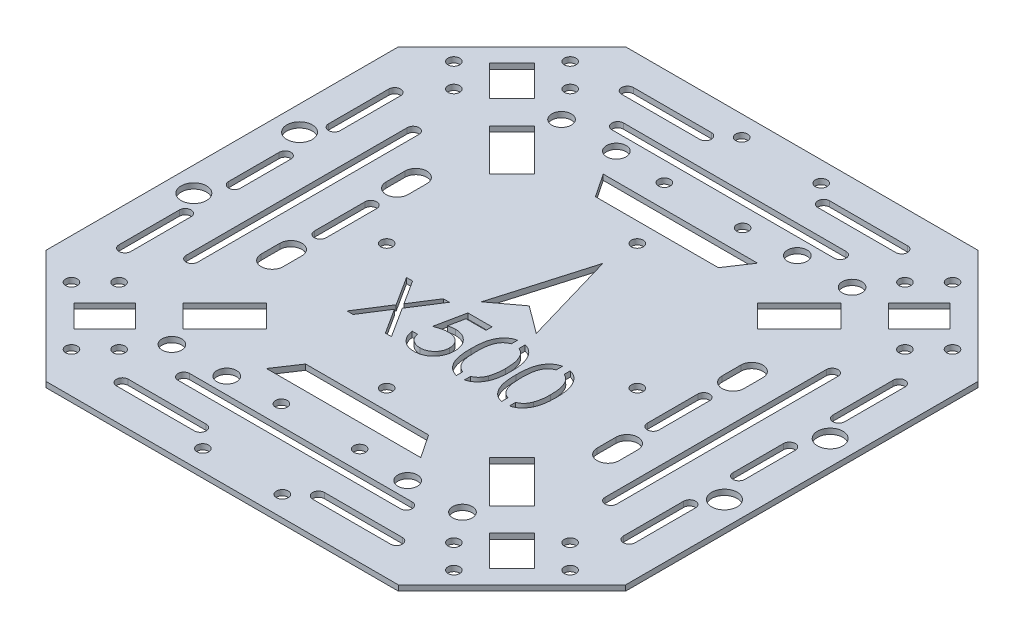
SolidWorks part; units mm, degrees
material "Thornel Mat VMA"
ref_plane "Front Plane" through (0, 0, 0) normal (0, 0, 1) x (1, 0, 0)
ref_plane "Top Plane" through (0, 0, 0) normal (0, 1, 0) x (1, 0, 0)
ref_plane "Right Plane" through (0, 0, 0) normal (1, 0, 0) x (0, 0, -1)
sketch "Sketch1" plane through (0, 0, 0) normal (0, 1, 0) x (1, 0, 0)
  line L0 (-74, 45) -> (-45, 74)
  line L1 (-45, 74) -> (45, 74)
  line L2 (-74, 45) -> (-74, -45)
  line L3 (-45, -74) -> (45, -74)
  line L4 (74, 45) -> (74, -45)
  line L5 (45, 74) -> (74, 45)
  line L6 (74, -45) -> (45, -74)
  line L7 (-45, -74) -> (-74, -45)
  line L8 (0, -51.6391) -> (0, 51.6391) construction
  line L9 (-43.1025, 0) -> (43.1025, 0) construction
  point P0 (0, -74)
  point P11 (0, 74)
  point P12 (-74, 0)
  point P15 (74, 0)
  dimension "D1" = 148
  dimension "D2" = 90
  dimension "D3" = 45
extrude "Boss-Extrude1" add sketch "Sketch1" along normal mid plane 1.4
sketch "Sketch3" plane through (0, 0.7, 0) normal (0, 1, 0) x (1, 0, 0)
  line L0 (-50.9087, 45.1811) -> (-58.7575, 53.03)
  line L1 (-50.9087, 45.1811) -> (-45.1811, 50.9087)
  line L2 (-58.7575, 53.03) -> (-53.03, 58.7575)
  line L3 (-45.1811, 50.9087) -> (-53.03, 58.7575)
  line L4 (-44.8982, 39.1707) -> (-34.2209, 28.4934)
  line L5 (-44.8982, 39.1707) -> (-39.1707, 44.8982)
  line L6 (-34.2209, 28.4934) -> (-28.4934, 34.2209)
  line L7 (-39.1707, 44.8982) -> (-28.4934, 34.2209)
  line L8 (0, 0) -> (-48.0449, 48.0449) construction
  line L9 (-63.6719, 48.8227) -> (-57.5908, 42.7416) construction
  line L10 (-45, 74) -> (-74, 45) construction
  line L11 (-48.8227, 63.6719) -> (-42.7416, 57.5908) construction
  line L12 (-63.6719, 48.8227) -> (-48.8227, 63.6719) construction
  line L13 (45.1811, 50.9087) -> (53.03, 58.7575)
  line L14 (45.1811, 50.9087) -> (50.9087, 45.1811)
  line L15 (53.03, 58.7575) -> (58.7575, 53.03)
  line L16 (50.9087, 45.1811) -> (58.7575, 53.03)
  line L17 (39.1707, 44.8982) -> (28.4934, 34.2209)
  line L18 (39.1707, 44.8982) -> (44.8982, 39.1707)
  line L19 (28.4934, 34.2209) -> (34.2209, 28.4934)
  line L20 (44.8982, 39.1707) -> (34.2209, 28.4934)
  line L21 (48.8227, 63.6719) -> (42.7416, 57.5908) construction
  line L22 (63.6719, 48.8227) -> (57.5908, 42.7416) construction
  line L23 (48.8227, 63.6719) -> (63.6719, 48.8227) construction
  line L24 (50.9087, -45.1811) -> (58.7575, -53.03)
  line L25 (50.9087, -45.1811) -> (45.1811, -50.9087)
  line L26 (58.7575, -53.03) -> (53.03, -58.7575)
  line L27 (45.1811, -50.9087) -> (53.03, -58.7575)
  line L28 (44.8982, -39.1707) -> (34.2209, -28.4934)
  line L29 (44.8982, -39.1707) -> (39.1707, -44.8982)
  line L30 (34.2209, -28.4934) -> (28.4934, -34.2209)
  line L31 (39.1707, -44.8982) -> (28.4934, -34.2209)
  line L32 (63.6719, -48.8227) -> (57.5908, -42.7416) construction
  line L33 (48.8227, -63.6719) -> (42.7416, -57.5908) construction
  line L34 (63.6719, -48.8227) -> (48.8227, -63.6719) construction
  line L35 (-45.1811, -50.9087) -> (-53.03, -58.7575)
  line L36 (-45.1811, -50.9087) -> (-50.9087, -45.1811)
  line L37 (-53.03, -58.7575) -> (-58.7575, -53.03)
  line L38 (-50.9087, -45.1811) -> (-58.7575, -53.03)
  line L39 (-39.1707, -44.8982) -> (-28.4934, -34.2209)
  line L40 (-39.1707, -44.8982) -> (-44.8982, -39.1707)
  line L41 (-28.4934, -34.2209) -> (-34.2209, -28.4934)
  line L42 (-44.8982, -39.1707) -> (-34.2209, -28.4934)
  line L43 (-48.8227, -63.6719) -> (-42.7416, -57.5908) construction
  line L44 (-63.6719, -48.8227) -> (-57.5908, -42.7416) construction
  line L45 (-48.8227, -63.6719) -> (-63.6719, -48.8227) construction
  line L46 (0, -0.77) -> (0, 0.77) construction
  line L47 (-0.77, 0) -> (0.77, 0) construction
  circle A0 centre (-48.8227, 63.6719) radius 1.5
  circle A1 centre (-63.6719, 48.8227) radius 1.5
  circle A2 centre (-57.5908, 42.7416) radius 1.5
  circle A3 centre (-42.7416, 57.5908) radius 1.5
  circle A4 centre (63.6719, 48.8227) radius 1.5
  circle A5 centre (48.8227, 63.6719) radius 1.5
  circle A6 centre (42.7416, 57.5908) radius 1.5
  circle A7 centre (57.5908, 42.7416) radius 1.5
  circle A8 centre (48.8227, -63.6719) radius 1.5
  circle A9 centre (63.6719, -48.8227) radius 1.5
  circle A10 centre (57.5908, -42.7416) radius 1.5
  circle A11 centre (42.7416, -57.5908) radius 1.5
  circle A12 centre (-63.6719, -48.8227) radius 1.5
  circle A13 centre (-48.8227, -63.6719) radius 1.5
  circle A14 centre (-42.7416, -57.5908) radius 1.5
  circle A15 centre (-57.5908, -42.7416) radius 1.5
  point P20 (-48.0449, 48.0449)
  point P21 (-55.8938, 55.8938)
  point P22 (-42.0345, 42.0345)
  point P23 (-31.3572, 31.3572)
  point P27 (-59.5, 59.5)
  point P77 (0, 0)
  dimension "D7" = 3
  dimension "D1" = 8.5
  dimension "D2" = 5.1
  dimension "D3" = 11.1
  dimension "D4" = 15.1
  dimension "D5" = 8.1
  dimension "D6" = 8.1
  dimension "D8" = 21
  dimension "D9" = 10.5
  dimension "D10" = 4.6
  dimension "D11" = 8.6
  dimension "D12" = 4
extrude "Cut-Extrude1" cut sketch "Sketch3" against normal through all
sketch "Sketch4" plane through (0, 0.7, 0) normal (0, 1, 0) x (1, 0, 0)
  line L0 (-53.5, 28.25) -> (-53.5, -28.25) construction
  line L3 (-52, 28.25) -> (-52, -28.25)
  line L6 (-55, 28.25) -> (-55, -28.25)
  line L9 (-64.4, 34.45) -> (-64.4, 19.05) construction
  line L12 (-62.9, 34.45) -> (-62.9, 19.05)
  line L15 (-65.9, 34.45) -> (-65.9, 19.05)
  line L18 (-64.4, -19.05) -> (-64.4, -34.45) construction
  line L21 (-74, 45) -> (-74, -45) construction
  line L22 (-62.9, -19.05) -> (-62.9, -34.45)
  line L23 (-65.9, -19.05) -> (-65.9, -34.45)
  line L24 (-64.4, 6.45) -> (-64.4, -6.45) construction
  line L25 (-62.9, 6.45) -> (-62.9, -6.45)
  line L26 (-65.9, 6.45) -> (-65.9, -6.45)
  line L27 (-42.9, 18.35) -> (-42.9, 13.55) construction
  line L28 (-40.1, 18.35) -> (-40.1, 13.55)
  line L29 (-45.7, 18.35) -> (-45.7, 13.55)
  line L30 (-42.5, 6.45) -> (-42.5, -6.45) construction
  line L31 (-41, 6.45) -> (-41, -6.45)
  line L32 (-44, 6.45) -> (-44, -6.45)
  line L33 (-42.9, -13.55) -> (-42.9, -18.35) construction
  line L34 (-40.1, -13.55) -> (-40.1, -18.35)
  line L35 (-45.7, -13.55) -> (-45.7, -18.35)
  line L36 (-0.77, 0) -> (0.77, 0) construction
  line L37 (-67.75, 13.5) -> (-67.75, -13.5) construction
  line L38 (-42.9, 13.55) -> (-42.9, -13.55) construction
  line L39 (0, -0.77) -> (0, 0.77) construction
  line L40 (53.5, 28.25) -> (53.5, -28.25) construction
  line L41 (52, 28.25) -> (52, -28.25)
  line L42 (55, 28.25) -> (55, -28.25)
  line L43 (64.4, 34.45) -> (64.4, 19.05) construction
  line L44 (62.9, 34.45) -> (62.9, 19.05)
  line L45 (65.9, 34.45) -> (65.9, 19.05)
  line L46 (64.4, -19.05) -> (64.4, -34.45) construction
  line L47 (62.9, -19.05) -> (62.9, -34.45)
  line L48 (65.9, -19.05) -> (65.9, -34.45)
  line L49 (64.4, 6.45) -> (64.4, -6.45) construction
  line L50 (62.9, 6.45) -> (62.9, -6.45)
  line L51 (65.9, 6.45) -> (65.9, -6.45)
  line L52 (42.9, 18.35) -> (42.9, 13.55) construction
  line L53 (40.1, 18.35) -> (40.1, 13.55)
  line L54 (45.7, 18.35) -> (45.7, 13.55)
  line L55 (42.5, 6.45) -> (42.5, -6.45) construction
  line L56 (41, 6.45) -> (41, -6.45)
  line L57 (44, 6.45) -> (44, -6.45)
  line L58 (42.9, -13.55) -> (42.9, -18.35) construction
  line L59 (40.1, -13.55) -> (40.1, -18.35)
  line L60 (45.7, -13.55) -> (45.7, -18.35)
  line L61 (42.9, 13.55) -> (42.9, -13.55) construction
  line L62 (67.75, 13.5) -> (67.75, -13.5) construction
  arc A17 (-52, 28.25) -> (-55, 28.25) centre (-53.5, 28.25) ccw
  arc A18 (-55, -28.25) -> (-52, -28.25) centre (-53.5, -28.25) ccw
  arc A19 (-62.9, 34.45) -> (-65.9, 34.45) centre (-64.4, 34.45) ccw
  arc A20 (-65.9, 19.05) -> (-62.9, 19.05) centre (-64.4, 19.05) ccw
  arc A21 (-62.9, -19.05) -> (-65.9, -19.05) centre (-64.4, -19.05) ccw
  arc A22 (-65.9, -34.45) -> (-62.9, -34.45) centre (-64.4, -34.45) ccw
  arc A23 (-62.9, 6.45) -> (-65.9, 6.45) centre (-64.4, 6.45) ccw
  arc A24 (-65.9, -6.45) -> (-62.9, -6.45) centre (-64.4, -6.45) ccw
  arc A25 (-40.1, 18.35) -> (-45.7, 18.35) centre (-42.9, 18.35) ccw
  arc A26 (-45.7, 13.55) -> (-40.1, 13.55) centre (-42.9, 13.55) ccw
  arc A27 (-41, 6.45) -> (-44, 6.45) centre (-42.5, 6.45) ccw
  arc A28 (-44, -6.45) -> (-41, -6.45) centre (-42.5, -6.45) ccw
  arc A29 (-40.1, -13.55) -> (-45.7, -13.55) centre (-42.9, -13.55) ccw
  arc A30 (-45.7, -18.35) -> (-40.1, -18.35) centre (-42.9, -18.35) ccw
  circle A31 centre (-67.75, 13.5) radius 3.25
  circle A32 centre (-67.75, -13.5) radius 3.25
  circle A33 centre (-32, 0) radius 1.5
  arc A34 (52, 28.25) -> (55, 28.25) centre (53.5, 28.25) cw
  arc A35 (55, -28.25) -> (52, -28.25) centre (53.5, -28.25) cw
  arc A36 (62.9, 34.45) -> (65.9, 34.45) centre (64.4, 34.45) cw
  arc A37 (65.9, 19.05) -> (62.9, 19.05) centre (64.4, 19.05) cw
  arc A38 (62.9, -19.05) -> (65.9, -19.05) centre (64.4, -19.05) cw
  arc A39 (65.9, -34.45) -> (62.9, -34.45) centre (64.4, -34.45) cw
  arc A40 (62.9, 6.45) -> (65.9, 6.45) centre (64.4, 6.45) cw
  arc A41 (65.9, -6.45) -> (62.9, -6.45) centre (64.4, -6.45) cw
  arc A42 (40.1, 18.35) -> (45.7, 18.35) centre (42.9, 18.35) cw
  arc A43 (45.7, 13.55) -> (40.1, 13.55) centre (42.9, 13.55) cw
  arc A44 (41, 6.45) -> (44, 6.45) centre (42.5, 6.45) cw
  arc A45 (44, -6.45) -> (41, -6.45) centre (42.5, -6.45) cw
  arc A46 (40.1, -13.55) -> (45.7, -13.55) centre (42.9, -13.55) cw
  arc A47 (45.7, -18.35) -> (40.1, -18.35) centre (42.9, -18.35) cw
  circle A48 centre (32, 0) radius 1.5
  circle A49 centre (67.75, -13.5) radius 3.25
  circle A50 centre (67.75, 13.5) radius 3.25
  point P2 (-53.5, 0)
  point P7 (-64.4, 26.75)
  point P14 (-64.4, -26.75)
  point P21 (-64.4, 0)
  point P28 (-42.9, 15.95)
  point P35 (-42.5, 0)
  point P42 (-42.9, -15.95)
  point P57 (-67.75, 0)
  point P60 (-42.9, 0)
  point P67 (53.5, 0)
  point P74 (64.4, 26.75)
  point P81 (64.4, -26.75)
  point P88 (64.4, 0)
  point P95 (42.9, 15.95)
  point P102 (42.5, 0)
  point P109 (42.9, -15.95)
  dimension "D9" = 6.5
  dimension "D18" = 3
  dimension "D1" = 3
  dimension "D2" = 8.1
  dimension "D3" = 12.6
  dimension "D4" = 12.6
  dimension "D5" = 12.9
  dimension "D6" = 15.4
  dimension "D7" = 19
  dimension "D8" = 56.5
  dimension "D10" = 6.25
  dimension "D11" = 27
  dimension "D12" = 30
  dimension "D13" = 12.9
  dimension "D14" = 5.6
  dimension "D15" = 4.8
  dimension "D16" = 28.3
  dimension "D17" = 27.1
  dimension "D19" = 42
extrude "Cut-Extrude2" cut sketch "Sketch4" against normal through all
sketch "Sketch5" plane through (0, 0.7, 0) normal (0, 1, 0) x (1, 0, 0)
  line L0 (-35, 64.5) -> (-15.1, 64.5) construction
  line L1 (-35, 66) -> (-15.1, 66)
  line L2 (-35, 63) -> (-15.1, 63)
  line L3 (15.1, 64.5) -> (35, 64.5) construction
  line L4 (15.1, 66) -> (35, 66)
  line L5 (15.1, 63) -> (35, 63)
  line L6 (-28.4, 55.4) -> (28.4, 55.4) construction
  line L7 (-28.4, 56.9) -> (28.4, 56.9)
  line L8 (-28.4, 53.9) -> (28.4, 53.9)
  line L9 (-19.7, 43) -> (-15.7, 37)
  line L10 (-15.7, 37) -> (15.7, 37)
  line L11 (15.7, 37) -> (19.7, 43)
  line L12 (19.7, 43) -> (-19.7, 43)
  line L13 (0, -0.77) -> (0, 0.77) construction
  line L14 (45, 74) -> (-45, 74) construction
  line L15 (-15.1, 64.5) -> (15.1, 64.5) construction
  line L16 (-10.15, 68.8) -> (10.15, 68.8) construction
  line L17 (-37.1, 49.75) -> (37.1, 49.75) construction
  line L18 (-10, 48.9) -> (10, 48.9) construction
  line L19 (-0.77, 0) -> (0.77, 0) construction
  line L20 (-35, -64.5) -> (-15.1, -64.5) construction
  line L21 (-35, -66) -> (-15.1, -66)
  line L22 (-35, -63) -> (-15.1, -63)
  line L23 (15.1, -64.5) -> (35, -64.5) construction
  line L24 (15.1, -66) -> (35, -66)
  line L25 (15.1, -63) -> (35, -63)
  line L26 (-28.4, -55.4) -> (28.4, -55.4) construction
  line L27 (-28.4, -56.9) -> (28.4, -56.9)
  line L28 (-28.4, -53.9) -> (28.4, -53.9)
  line L29 (-10, -48.9) -> (10, -48.9) construction
  line L30 (-37.1, -49.75) -> (37.1, -49.75) construction
  line L31 (-10.15, -68.8) -> (10.15, -68.8) construction
  line L32 (-15.1, -64.5) -> (15.1, -64.5) construction
  line L33 (19.7, -43) -> (-19.7, -43)
  line L34 (15.7, -37) -> (19.7, -43)
  line L35 (-15.7, -37) -> (15.7, -37)
  line L36 (-19.7, -43) -> (-15.7, -37)
  arc A0 (-35, 66) -> (-35, 63) centre (-35, 64.5) ccw
  arc A1 (-15.1, 63) -> (-15.1, 66) centre (-15.1, 64.5) ccw
  arc A2 (15.1, 66) -> (15.1, 63) centre (15.1, 64.5) ccw
  arc A3 (35, 63) -> (35, 66) centre (35, 64.5) ccw
  arc A4 (-28.4, 56.9) -> (-28.4, 53.9) centre (-28.4, 55.4) ccw
  arc A5 (28.4, 53.9) -> (28.4, 56.9) centre (28.4, 55.4) ccw
  circle A6 centre (-37.1, 49.75) radius 2.5
  circle A7 centre (-23.1, 49.75) radius 2.5
  circle A8 centre (-10, 48.9) radius 1.5
  circle A9 centre (10, 48.9) radius 1.5
  circle A10 centre (23.1, 49.75) radius 2.5
  circle A11 centre (37.1, 49.75) radius 2.5
  circle A12 centre (10.15, 68.8) radius 1.5
  circle A13 centre (-10.15, 68.8) radius 1.5
  circle A14 centre (0, 32) radius 1.5
  arc A15 (-35, -66) -> (-35, -63) centre (-35, -64.5) cw
  arc A16 (-15.1, -63) -> (-15.1, -66) centre (-15.1, -64.5) cw
  arc A17 (15.1, -66) -> (15.1, -63) centre (15.1, -64.5) cw
  arc A18 (35, -63) -> (35, -66) centre (35, -64.5) cw
  arc A19 (-28.4, -56.9) -> (-28.4, -53.9) centre (-28.4, -55.4) cw
  arc A20 (28.4, -53.9) -> (28.4, -56.9) centre (28.4, -55.4) cw
  circle A21 centre (0, -32) radius 1.5
  circle A22 centre (-10.15, -68.8) radius 1.5
  circle A23 centre (10.15, -68.8) radius 1.5
  circle A24 centre (37.1, -49.75) radius 2.5
  circle A25 centre (23.1, -49.75) radius 2.5
  circle A26 centre (10, -48.9) radius 1.5
  circle A27 centre (-10, -48.9) radius 1.5
  circle A28 centre (-23.1, -49.75) radius 2.5
  circle A29 centre (-37.1, -49.75) radius 2.5
  point P2 (-25.05, 64.5)
  point P7 (25.05, 64.5)
  point P14 (0, 55.4)
  point P45 (0, 64.5)
  point P46 (0, 49.75)
  point P47 (0, 68.8)
  point P50 (0, 48.9)
  point P53 (0, 43)
  point P59 (-25.05, -64.5)
  point P66 (25.05, -64.5)
  point P73 (0, -55.4)
  dimension "D1" = 3
  dimension "D4" = 5
  dimension "D2" = 19.9
  dimension "D3" = 30.2
  dimension "D5" = 8
  dimension "D6" = 20.3
  dimension "D7" = 5.2
  dimension "D8" = 14
  dimension "D9" = 14
  dimension "D10" = 74.2
  dimension "D11" = 24.25
  dimension "D12" = 17.1
  dimension "D13" = 56.8
  dimension "D14" = 20
  dimension "D15" = 25.1
  dimension "D16" = 6
  dimension "D17" = 39.4
  dimension "D18" = 31.4
  dimension "D19" = 31
  dimension "D20" = 42
extrude "Cut-Extrude3" cut sketch "Sketch5" against normal through all
sketch "Sketch6" plane through (0, 0.7, 0) normal (0, 1, 0) x (1, 0, 0)
  line L0 (0, 23.2) -> (-7, -0.8)
  line L1 (0, -0.77) -> (0, 0.77) construction
  line L2 (-7, -0.8) -> (0, 4.4)
  line L3 (0, 4.4) -> (7, -0.8)
  line L4 (7, -0.8) -> (0, 23.2)
  line L5 (-22.8147, -19.9856) -> (22.8147, -19.9856) construction
  circle A0 centre (0, 32) radius 1.5 construction
  text T0 "X500" font "Century Gothic" height 15
  point P11 (0, -19.9856)
  dimension "D4" = 8.8
  dimension "D1" = 24
  dimension "D2" = 5.2
  dimension "D3" = 14
extrude "Cut-Extrude4" cut sketch "Sketch6" against normal through all
sketch "Sketch7" plane through (0, 0.7, 0) normal (0, 1, 0) x (1, 0, 0)
  line L0 (15.7, -37) -> (-15.7, -37) construction
  line L1 (6.1, -2) -> (8.1, -2)
  line L2 (6.1, -2) -> (6.1, -22)
  line L3 (6.1, -22) -> (8.1, -22)
  line L4 (8.1, -2) -> (8.1, -22)
  line L5 (17.6, -2) -> (19.6, -2)
  line L6 (17.6, -2) -> (17.6, -22)
  line L7 (17.6, -22) -> (19.6, -22)
  line L8 (19.6, -2) -> (19.6, -22)
  line L9 (0, -0.77) -> (0, 0.77) construction
  dimension "D1" = 2
  dimension "D2" = 15
  dimension "D3" = 20
  dimension "D4" = 6.1
  dimension "D5" = 17.6
extrude "Boss-Extrude2" add sketch "Sketch7" against normal up to surface (1.4 mm away) up to face at (0, -0.7, -6.5)
